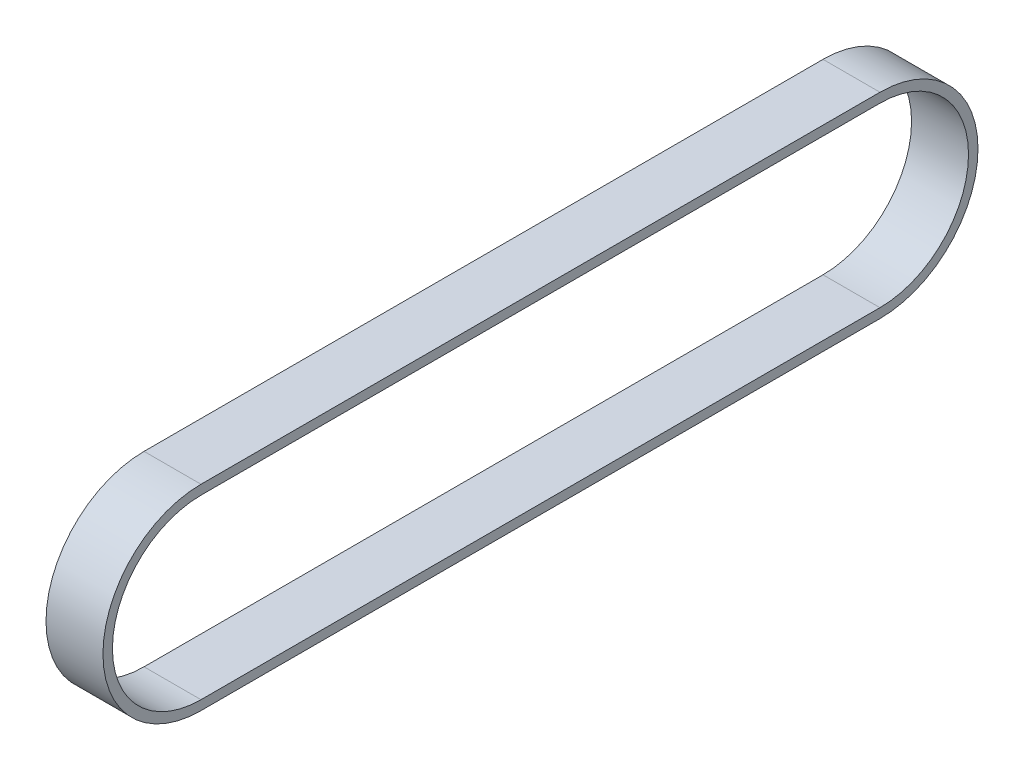
SolidWorks part; units mm, degrees
material "Rubber"
ref_plane "Frente" through (0, 0, 0) normal (0, 0, 1) x (1, 0, 0)
ref_plane "Topo" through (0, 0, 0) normal (0, 1, 0) x (1, 0, 0)
ref_plane "Lateral" through (0, 0, 0) normal (1, 0, 0) x (0, 0, -1)
sketch "Sketch1" plane through (0, 0, 0) normal (1, 0, 0) x (0, 0, -1)
  line L0 (-71.545, 9.33) -> (0, 9.33)
  line L1 (0, 9.33) -> (0, -9.33) construction
  line L2 (0, -9.33) -> (-71.545, -9.33)
  line L3 (-71.545, -9.33) -> (-71.545, 9.33) construction
  arc A0 (0, -9.33) -> (0, 9.33) centre (0, 0) ccw
  arc A1 (-71.545, 9.33) -> (-71.545, -9.33) centre (-71.545, 0) ccw
  dimension "D1" = 9.33
  dimension "D2" = 29.3111
  dimension "D3" = 71.545
extrude "Extrude-Thin1" add sketch "Sketch1" along normal mid plane 6 thin thin type one direction wall 1
